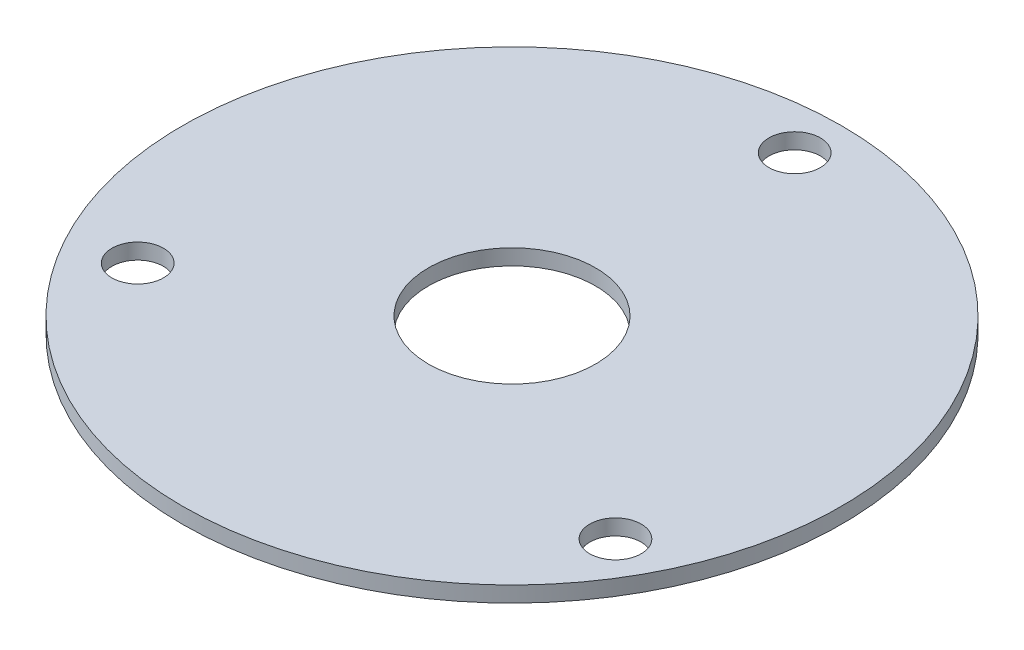
SolidWorks part; units mm, degrees
ref_plane "Front Plane" through (0, 0, 0) normal (0, 0, 1) x (1, 0, 0)
ref_plane "Top Plane" through (0, 0, 0) normal (0, 1, 0) x (1, 0, 0)
ref_plane "Right Plane" through (0, 0, 0) normal (1, 0, 0) x (0, 0, -1)
sketch "Sketch2" plane through (0, 0, 0) normal (0, 1, 0) x (1, 0, 0)
  circle A0 centre (0, 0) radius 52.5
  circle A1 centre (0, 0) radius 13.3
  dimension "D1" = 105
  dimension "D2" = 26.6
extrude "Boss-Extrude1" add sketch "Sketch2" along normal blind 2.5
sketch "Sketch3" plane through (0, 2.5, 0) normal (0, 1, 0) x (1, 0, 0)
  line L1 (0, 45.0333) -> (-39, -22.5167) construction
  line L2 (-39, -22.5167) -> (39, -22.5167) construction
  line L3 (39, -22.5167) -> (0, 45.0333) construction
  circle A0 centre (0, 0) radius 22.5167 construction
  circle A1 centre (0, 45.0333) radius 4.1
  circle A2 centre (39, -22.5167) radius 4.1
  circle A3 centre (-37.1139, -22.5167) radius 4.1
  dimension "D2" = 8.2
  dimension "D3" = 8.2
  dimension "D4" = 8.2
  dimension "D1" = 78
extrude "Cut-Extrude1" cut sketch "Sketch3" against normal through all
